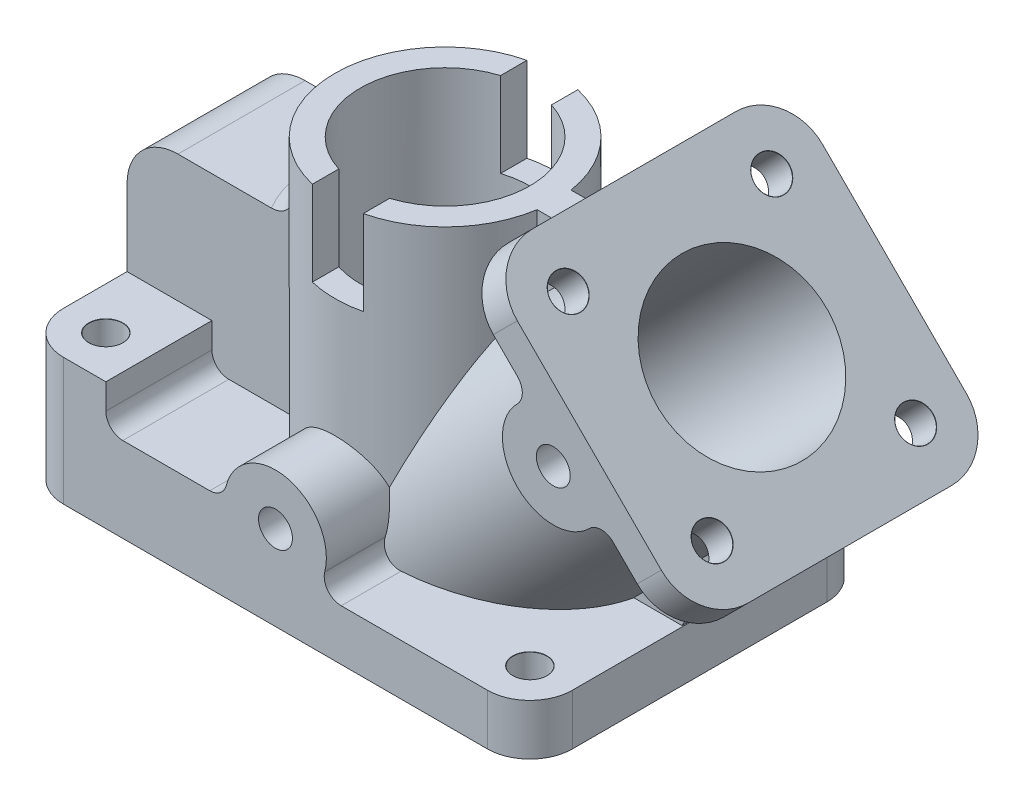
SolidWorks part; units mm, degrees
ref_plane "Front Plane" through (0, 0, 0) normal (0, 0, 1) x (1, 0, 0)
ref_plane "Top Plane" through (0, 0, 0) normal (0, 1, 0) x (1, 0, 0)
ref_plane "Right Plane" through (0, 0, 0) normal (1, 0, 0) x (0, 0, -1)
sketch "Croquis16" plane through (0, 0, 0) normal (0, 0, 1) x (1, 0, 0)
  line L0 (0, 0) -> (0, 15)
  line L1 (0, 15) -> (10, 15)
  line L2 (10, 15) -> (10, 10)
  line L3 (10, 10) -> (24, 10)
  line L4 (34.4721, 6) -> (60, 6)
  line L5 (60, 6) -> (60, 0)
  line L6 (60, 0) -> (0, 0)
  arc A0 (24, 10) -> (34.4721, 6) centre (30, 10) cw
  circle A1 centre (30, 10) radius 2
  dimension "D4" = 6
  dimension "D8" = 4
  dimension "D1" = 15
  dimension "D2" = 60
  dimension "D3" = 6
  dimension "D5" = 10
  dimension "D6" = 10
  dimension "D7" = 30
extrude "Saliente-Extruir8" add sketch "Croquis16" along normal mid plane 40
fillet "Redondeo1" radius 2 3 edges at (24, 10, 0) (34.4721, 6, 0) (10, 10, 0)
sketch "Croquis17" plane through (0, 0, 0) normal (0, -1, 0) x (1, 0, 0)
  line L0 (0, 20) -> (0, -20) construction
  circle A0 centre (30, 0) radius 13
  dimension "D2" = 26
  dimension "D1" = 30
fillet "Redondeo2" radius 5 4 edges at (0, 7.5, -20) (60, 3, -20) (60, 3, 20) (0, 7.5, 20)
extrude "Saliente-Extruir9" add sketch "Croquis17" against normal blind 40
sketch "Croquis18" plane through (0, 0, 0) normal (0, 0, 1) x (1, 0, 0)
  line L0 (0, 7.5) -> (0, 30)
  line L1 (0, 0) -> (0, 15) construction
  line L2 (0, 30) -> (21.0979, 30)
  line L3 (21.0979, 30) -> (21.0979, 7.5)
  line L4 (21.0979, 7.5) -> (0, 7.5)
  dimension "D1" = 30
extrude "Saliente-Extruir10" add sketch "Croquis18" along normal mid plane 15
fillet "Redondeo3" radius 2 1 edges at (17, 30, 0)
fillet "Redondeo4" radius 6 1 edges at (0, 30, 0)
sketch "Croquis19" plane through (0, 0, 0) normal (0, 0, 1) x (1, 0, 0)
  line L0 (30, 0) -> (65, 35) construction
  line L1 (5, 0) -> (55, 0) construction
  line L2 (30, 0) -> (30, 39.4091) construction
  line L3 (55, 0) -> (60, 0) construction
  dimension "D1" = 45
  dimension "D2" = 35
ref_plane "Plano3" through (65, 35, 0) normal (0.7071, 0.7071, 0) x (0, 0, -1)
sketch "Croquis20" plane through (65, 35, 0) normal (0.7071, 0.7071, 0) x (0, 0, -1)
  line L0 (0, 0) -> (0, 27.8664) construction
  line L1 (18, -18) -> (-18, -18)
  line L2 (18, -18) -> (18, 18)
  line L3 (18, 18) -> (-18, 18)
  line L4 (-18, -18) -> (-18, 18)
  line L5 (18, -18) -> (-18, 18) construction
  line L6 (18, 18) -> (-18, -18) construction
  point P0 (0, 0)
  dimension "D1" = 36
extrude "Saliente-Extruir12" add sketch "Croquis20" against normal blind 4 separate body
sketch "Croquis21" plane through (50, 50, 0) normal (0.7071, 0.7071, 0) x (0, 0, -1)
  line L0 (0, -21.2132) -> (0, 6.6532) construction
  circle A0 centre (0, -21.2132) radius 10
  dimension "D1" = 20
extrude "Saliente-Extruir13" add sketch "Croquis21" against normal blind 41
sketch "Croquis22" plane through (0, 0, 18) normal (0, 0, 1) x (1, 0, 0)
  line L0 (30, 0) -> (65, 35) construction
  line L1 (84.25, 15.75) -> (45.75, 54.25) construction
  circle A0 centre (60.7574, 30.7574) radius 6
  circle A1 centre (60.7574, 30.7574) radius 2
  dimension "D1" = 6
  dimension "D2" = 12
  dimension "D3" = 4
extrude "Saliente-Extruir14" add sketch "Croquis22" against normal blind 36
fillet "Redondeo5" radius 6 4 edges at (76.3137, 20.8579, 18) (50.8579, 46.3137, -18) (76.3137, 20.8579, -18) (50.8579, 46.3137, 18)
fillet "Redondeo6" radius 2 4 edges at (58.1716, 36.1716, 13.1231) (66.1716, 28.1716, 13.1231) (58.1716, 36.1716, -13.1231) (66.1716, 28.1716, -13.1231)
hole_wizard "Ø4.0mm Dowel Hole1" positions "Croquis3D3" profile "Croquis27" hole size "Ø4.0" standard "ISO"
sketch3d "Croquis3D3"
  line L0 (53.6863, 40.6569, -12) -> (56.5147, 43.4853, -12) construction
  line L1 (70.6569, 23.6863, -12) -> (73.4853, 26.5147, -12) construction
  line L2 (70.6569, 23.6863, 12) -> (73.4853, 26.5147, 12) construction
  line L3 (53.6863, 40.6569, 12) -> (56.5147, 43.4853, 12) construction
  point P0 (56.5147, 43.4853, -12)
  point P4 (73.4853, 26.5147, -12)
  point P8 (73.4853, 26.5147, 12)
  point P12 (56.5147, 43.4853, 12)
sketch "Croquis27" plane through (56.5147, 43.4853, -12) normal (0, 0, 1) x (-0.7071, 0.7071, 0)
  line L0 (0, 0) -> (0, 6.2017)
  line L1 (0, 6.2017) -> (2, 5)
  line L2 (2, 5) -> (2, 0.021)
  line L3 (2, 0.021) -> (2.025, 0)
  line L5 (2.025, 0) -> (0, 0)
  line L6 (-2, 0.021) -> (-2.025, 0) construction
  line L10 (0, 6.2017) -> (-2, 5) construction
  line L11 (0, -6.35) -> (0, 107.95) construction
  dimension "Hole Dia." = 4
  dimension "Hole Depth" = 5
  dimension "Near C'Sink Dia." = 4.05
  dimension "Near C'Sink Angle" = 100
  dimension "Drill Angle" = 118
hole_wizard "Ø4.0mm Dowel Hole2" positions "Croquis3D6" profile "Croquis30" hole size "Ø4.0" standard "ISO"
sketch3d "Croquis3D6"
  line L0 (5, 15, 15) -> (5, 0, 15) construction
  line L1 (5, 0, -15) -> (5, 15, -15) construction
  line L2 (55, 6, -15) -> (55, 0, -15) construction
  line L3 (55, 0, 15) -> (55, 6, 15) construction
  point P0 (5, 15, 15)
  point P4 (5, 15, -15)
  point P8 (55, 6, -15)
  point P12 (55, 6, 15)
sketch "Croquis30" plane through (5, 15, 15) normal (1, 0, 0) x (0, 0, 1)
  line L0 (0, 0) -> (0, 16.0624)
  line L1 (0, 16.0624) -> (2, 16.0624)
  line L2 (2, 16.0624) -> (2, 0.021)
  line L3 (2, 0.021) -> (2.025, 0)
  line L5 (2.025, 0) -> (0, 0)
  line L6 (-2, 0.021) -> (-2.025, 0) construction
  line L11 (0, -6.35) -> (0, 107.95) construction
  dimension "Thru Hole Dia." = 4
  dimension "Thru Hole Depth" = 16.0624
  dimension "Near C'Sink Dia." = 4.05
  dimension "Near C'Sink Angle" = 100
sketch "Croquis31" plane through (0, 0, 0) normal (0, 0, 1) x (1, 0, 0)
  line L0 (38.4685, 40) -> (56.3444, 40)
  line L1 (43, 40) -> (17, 40) construction
  line L2 (56.3444, 40) -> (56.3444, 24.9494)
  line L3 (56.3444, 24.9494) -> (38.4685, 24.9494)
  line L4 (38.4685, 24.9494) -> (38.4685, 40)
extrude "Saliente-Extruir15" add sketch "Croquis31" along normal mid plane 4
sketch "Croquis32" plane through (0, 0, 0) normal (0, 0, 1) x (1, 0, 0)
  line L0 (59.9483, 6.0704) -> (69.2426, 25.1005)
  line L1 (69.2426, 25.1005) -> (50.2126, 6.0704)
  line L2 (50.1421, 6) -> (69.2426, 25.1005) construction
  line L3 (50.2126, 6.0704) -> (59.9483, 6.0704)
extrude "Saliente-Extruir19" add sketch "Croquis32" along normal mid plane 4 separate body
sketch "Croquis33" plane through (50, 50, 0) normal (0.7071, 0.7071, 0) x (0, 0, -1)
  line L0 (0, -21.2132) -> (0, 6.6532) construction
  circle A0 centre (0, -21.2132) radius 13
  point P6 (0, 0)
  dimension "D1" = 26
extrude "Saliente-Extruir21" add sketch "Croquis33" against normal blind 42
sketch "Croquis34" plane through (50, 50, 0) normal (0.7071, 0.7071, 0) x (0, 0, -1)
  line L0 (0, -21.2132) -> (0, 6.6532) construction
  circle A0 centre (0, -21.2132) radius 10
  dimension "D1" = 20
extrude "Cortar-Extruir6" cut sketch "Croquis34" against normal through all
sketch "Croquis35" plane through (0, 0, 0) normal (0, 0, 1) x (1, 0, 0)
  line L0 (33, 30) -> (27, 30)
  line L1 (30, 0) -> (30, 39.4091) construction
  line L2 (27, 30) -> (27, 40)
  line L3 (42.8452, 40) -> (17, 40) construction
  line L4 (27, 40) -> (33, 40)
  line L5 (33, 40) -> (33, 30)
  point P3 (30, 30)
  point P9 (30, 31.9398)
  dimension "D1" = 6
  dimension "D2" = 10
extrude "Cortar-Extruir8" cut sketch "Croquis35" against normal mid plane 42
sketch "Croquis36" plane through (0, 40, 0) normal (0, 1, 0) x (1, 0, 0)
  circle A0 centre (30, 0) radius 10
  dimension "D1" = 20
extrude "Cortar-Extruir9" cut sketch "Croquis36" against normal through all
